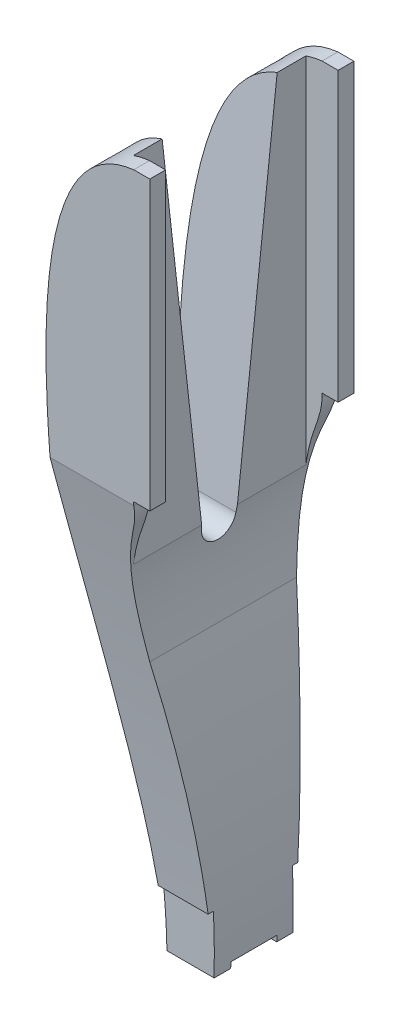
SolidWorks part; units mm, degrees
material "1060-H12"
ref_plane "Front Plane" through (0, 0, 0) normal (0, 0, 1) x (1, 0, 0)
ref_plane "Top Plane" through (0, 0, 0) normal (0, 1, 0) x (1, 0, 0)
ref_plane "Right Plane" through (0, 0, 0) normal (1, 0, 0) x (0, 0, -1)
ref_plane "Plane1" through (0, 35.6, 0) normal (0, 1, 0) x (-1, 0, 0)
sketch "Sketch1" plane through (0, 0, 0) normal (0, 0, 1) x (1, 0, 0)
  line L0 (5.6, 35.6) -> (5.6, -15)
  line L1 (-4.0881, -120.4081) -> (3.5407, -122.8051)
  spline S0 degree 3 poles (5.6, 35.6) (-12.3679, 33.5213) (-8.7824, -50.7826) (5.9542, -91.4515) (-4.0881, -120.4081) knots 0 0 0 0 0.405307 1 1 1 1
  spline S1 degree 2 poles (3.4094, -42.1161) (14.0214, -91.1985) (3.5407, -122.8051) knots 0 0 0 1 1 1
  spline S3 degree 3 poles (5.6, -15) (5.6, -17.2744) (1.6042, -25.848) (2.4158, -35.1136) (3.4094, -42.1161) knots 0 0 0 0 0.227789 0.9215 0.9215 0.9215 0.9215
extrude "Boss-Extrude2" add sketch "Sketch1" along normal blind 35.5
sketch "Sketch3" plane through (0, 0, 0) normal (1, 0, 0) x (0, 0, -1)
  line L0 (0, -14.9824) -> (29.6274, -14.9824)
  line L1 (0, -120.4081) -> (0, 35.6) construction
  line L3 (29.6274, -14.9824) -> (29.6274, -131.5725)
  line L4 (-12.75, -120.4081) -> (-22.7692, -120.4081)
  line L6 (29.6274, -131.5725) -> (-60.5471, -131.5725)
  line L7 (-35.5, 35.6) -> (-35.5, -120.4081) construction
  line L8 (-60.5471, -131.5725) -> (-60.5471, -14.9824)
  line L9 (-60.5471, -14.9824) -> (-35.5, -14.9824)
  spline S0 degree 3 poles (0, -14.9824) (-7.1912, -49.7586) (-11.4412, -85.1664) (-12.75, -120.4081) knots 0 0 0 0 1 1 1 1
  spline S1 degree 3 poles (-35.5, -14.9824) (-28.3088, -49.7586) (-24.078, -85.1664) (-22.7692, -120.4081) knots 0 0 0 0 1 1 1 1
extrude "Cut-Extrude1" cut sketch "Sketch3" against normal mid plane 35.5
sketch "Sketch4" plane through (5.6, 0, 0) normal (1, 0, 0) x (0, 0, -1)
  line L1 (-2.75, 35.6) -> (-32.75, 35.6)
  line L2 (-2.75, 35.6) -> (-2.75, -15)
  line L3 (0, -14.9824) -> (0, 35.6) construction
  line L4 (-32.75, 35.6) -> (-32.75, -15)
  line L5 (-35.4964, -15) -> (-0.0036, -15) construction
  line L8 (-32.75, -15) -> (-32.75, -32.0181)
  line L9 (-32.75, -32.0181) -> (-2.75, -32.0181)
  line L10 (-2.75, -15) -> (-2.75, -32.0181)
  dimension "D1" = 30
  dimension "D2" = 30
  dimension "D3" = 2.75
extrude "Cut-Extrude2" cut sketch "Sketch4" against normal blind 2.8
sketch "Sketch5" plane through (0, 35.6, 0) normal (0, 1, 0) x (1, 0, 0)
  line L1 (5.6, 0) -> (8.4, 0)
  line L2 (5.6, 0) -> (5.6, -2.75)
  line L3 (5.6, -2.75) -> (8.4, -2.75)
  line L4 (8.4, 0) -> (8.4, -2.75)
  line L6 (5.6, -35.5) -> (8.4, -35.5)
  line L7 (5.6, -35.5) -> (5.6, -32.75)
  line L8 (5.6, -32.75) -> (8.4, -32.75)
  line L9 (8.4, -35.5) -> (8.4, -32.75)
  dimension "D1" = 2.8
  dimension "D2" = 2.75
  dimension "D3" = 2.75
  dimension "D4" = 2.8
extrude "Boss-Extrude3" add sketch "Sketch5" against normal blind 50
sketch "Sketch6" plane through (0, 0, 0) normal (1, 0, 0) x (0, 0, -1)
  line L0 (-7.75, 34.9693) -> (-14.7818, -27.8088)
  line L1 (-2.75, 34.9693) -> (-32.75, 34.9693) construction
  line L2 (-20.7446, -27.8076) -> (-27.75, 34.9693)
  line L3 (-7.75, 34.9693) -> (-27.75, 34.9693)
  arc A0 (-20.7446, -27.8076) -> (-14.7818, -27.8088) centre (-17.7631, -27.4748) ccw
  circle A1 centre (0, 0) radius 1
extrude "Cut-Extrude3" cut sketch "Sketch6" against normal mid plane 30
ref_plane "Plane2" through (4.2977, -120.4081, 22.7692) normal (-0.2874, -0.9571, -0.0355) x (0.9578, -0.2872, -0.0107)
hole_wizard "Ø2.7 (2.7) Diameter Hole1" [suppressed] positions "Sketch8" profile "Sketch7" hole size "Ø2.7" standard "ISO"
sketch "Sketch8" plane through (0, 0, 35.5) normal (0, 0, 1) x (1, 0, 0)
  line L0 (8.4, -14.4) -> (8.4, 35.6) construction
  line L1 (5.6, 35.6) -> (8.4, 35.6) construction
  point P0 (5.6, 28.1)
  point P1 (5.6, 11.1)
  point P3 (5.6, -5.9)
  dimension "D1" = 2.8
  dimension "D2" = 2.8
  dimension "D3" = 2.8
  dimension "D4" = 41.5
  dimension "D5" = 7.5
  dimension "D6" = 24.5
sketch "Sketch7" plane through (5.6, 28.1, 35.5) normal (1, 0, 0) x (0, -1, 0)
  line L0 (0, 0) -> (0, 35.5)
  line L1 (0, 35.5) -> (1.35, 35.5)
  line L2 (1.35, 35.5) -> (1.35, 0)
  line L5 (1.35, 0) -> (0, 0)
  line L11 (0, -6.35) -> (0, 107.95) construction
  dimension "Thru Hole Dia." = 2.7
  dimension "Thru Hole Depth" = 35.5
hole_wizard "M3 Tapped Hole1" [suppressed] positions "Sketch10" profile "Sketch11" tap size "M3" standard "ISO"
sketch "Sketch10" plane through (0, 0, 35.5) normal (0, 0, 1) x (1, 0, 0)
  point P0 (4.5, -85)
sketch "Sketch11" plane through (4.5, -85, 35.5) normal (1, 0, 0) x (0, -1, 0)
  line L0 (0, 0) -> (0, 42.9602)
  line L1 (0, 42.9602) -> (1.25, 42.9602)
  line L2 (1.25, 42.9602) -> (1.25, 0)
  line L5 (1.25, 0) -> (0, 0)
  line L11 (0, -6.35) -> (0, 107.95) construction
  dimension "Thru Tap Drill Dia." = 2.5
  dimension "Thru Tap Drill Depth" = 42.9602
cosmetic thread "Hole Thread1" [suppressed] parameters "D2"=3
sketch "Sketch12" plane through (0, 0, 0) normal (1, 0, 0) x (0, 0, -1)
  line L0 (-9.3959, -80) -> (-10.8927, -80)
  line L1 (-10.8927, -80) -> (-10.8927, -90)
  line L2 (-10.8927, -90) -> (-9.3959, -90)
  line L3 (-9.3959, -90) -> (-9.3959, -80)
  line L4 (-24.6227, -80) -> (-24.6227, -90)
  line L5 (-24.6227, -90) -> (-26.1946, -90)
  line L6 (-26.1946, -90) -> (-26.1946, -80)
  line L7 (-26.1946, -80) -> (-24.6227, -80)
  spline S0 degree 3 poles (0, -14.9824) (-7.1912, -49.7586) (-11.4412, -85.1664) (-12.75, -120.4081) knots 0 0 0 0 1 1 1 1 construction
  spline S1 degree 3 poles (-22.7692, -120.4081) (-24.078, -85.1664) (-28.3088, -49.7586) (-35.5, -14.9824) knots 0 0 0 0 1 1 1 1 construction
  dimension "D1" = 90
  dimension "D2" = 10
extrude "Cut-Extrude4" cut sketch "Sketch12" along normal through all and the other way through all
sketch "Sketch14" plane through (0, 0, 10.8927) normal (0, 0, -1) x (-1, 0, 0)
  line L0 (-8.7203, -90) -> (6.2727, -90)
  line L1 (6.2727, -90) -> (6.2727, -124.0936)
  line L2 (6.2727, -124.0936) -> (-10.5411, -124.0936)
  line L3 (-10.5411, -124.0936) -> (-10.5411, -90)
  line L4 (-10.5411, -90) -> (-8.7203, -90)
extrude "Cut-Extrude5" cut sketch "Sketch14" against normal blind 20
sketch "Sketch15" plane through (0, -90, 0) normal (0, -1, 0) x (-1, 0, 0)
  line L2 (-8.7203, -10.8927) -> (-0.5063, -10.8927) construction
  line L5 (-5.2203, -13.7427) -> (-8.7203, -13.7427)
  line L6 (-8.7203, -24.6227) -> (-8.7203, -10.8927) construction
  line L7 (-5.2203, -21.7427) -> (-9.6234, -21.7427)
  line L8 (-9.6234, -21.7427) -> (-9.6234, -13.7427)
  line L9 (-9.6234, -13.7427) -> (-8.7203, -13.7427)
  arc A0 (-5.2203, -21.7427) -> (-5.2203, -13.7427) centre (-5.2203, -17.7427) ccw
  dimension "D1" = 8
  dimension "D2" = 6.85
  dimension "D3" = 3.5
extrude "Cut-Extrude6" cut sketch "Sketch15" against normal blind 1
sketch "Sketch16" plane through (0, 0, 35.5) normal (0, 0, 1) x (1, 0, 0)
  line L0 (171.0634, 145.588) -> (5.2203, -126.5) construction
